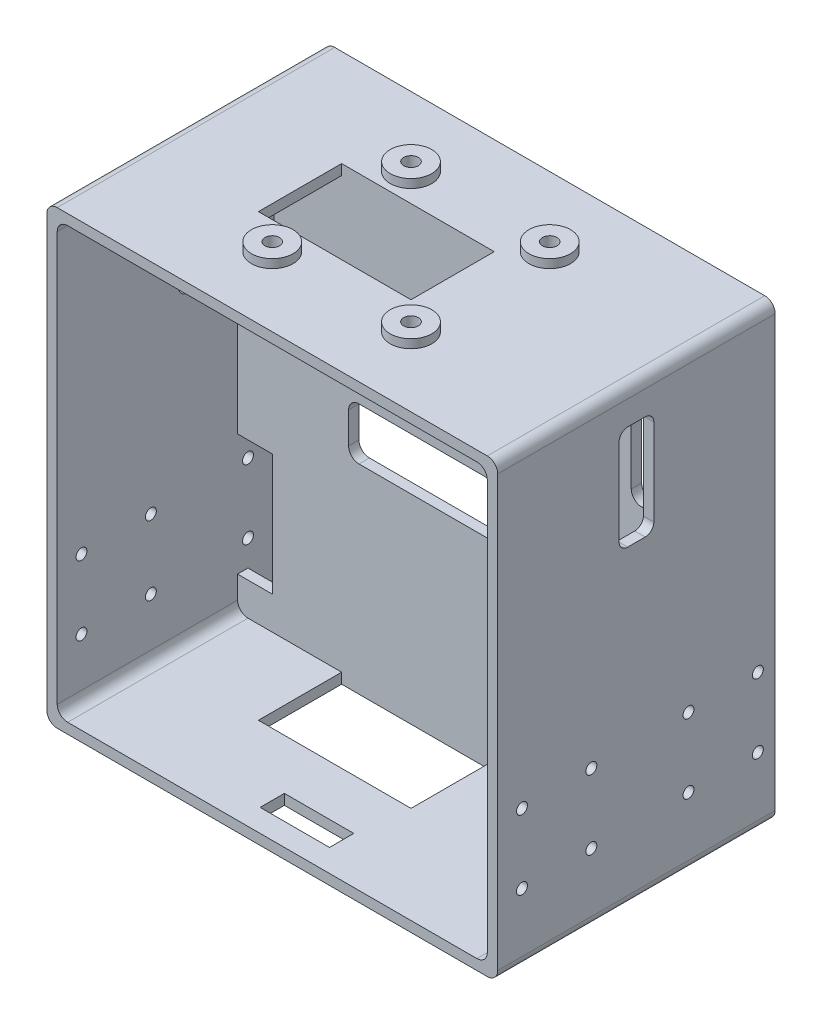
SolidWorks part; units mm, degrees
material "Du"
ref_plane "Front Plane" through (0, 0, 0) normal (0, 0, 1) x (1, 0, 0)
ref_plane "Top Plane" through (0, 0, 0) normal (0, 1, 0) x (1, 0, 0)
ref_plane "Right Plane" through (0, 0, 0) normal (1, 0, 0) x (0, 0, -1)
sketch "Sketch1" plane through (0, 0, 0) normal (0, 0, 1) x (1, 0, 0)
  line L1 (-65, 65) -> (65, 65)
  line L2 (-65, 65) -> (-65, -65)
  line L3 (-65, -65) -> (65, -65)
  line L4 (65, 65) -> (65, -65)
  line L5 (-65, 65) -> (65, -65) construction
  line L6 (-65, -65) -> (65, 65) construction
  line L7 (-62, 62) -> (62, 62)
  line L8 (-62, 62) -> (-62, -62)
  line L9 (-62, -62) -> (62, -62)
  line L10 (62, 62) -> (62, -62)
  line L11 (-62, 62) -> (62, -62) construction
  line L12 (-62, -62) -> (62, 62) construction
  point P0 (0, 0)
  point P6 (0, 0)
  dimension "D1" = 130
  dimension "D2" = 130
  dimension "D3" = 124
extrude "Boss-Extrude1" add sketch "Sketch1" along normal blind 80
fillet "Fillet1" radius 3 4 edges at (65, -65, 40) (-65, -65, 40) (-65, 65, 40) (65, 65, 40)
fillet "Fillet2" radius 3 4 edges at (62, -62, 40) (62, 62, 40) (-62, 62, 40) (-62, -62, 40)
sketch "Sketch2" plane through (0, -65, 0) normal (0, -1, 0) x (1, 0, 0)
  line L0 (-65, 0) -> (-65, 80) construction
  line L1 (-32, 52) -> (12, 52)
  line L2 (-32, 52) -> (-32, 28)
  line L3 (-32, 28) -> (12, 28)
  line L4 (12, 52) -> (12, 28)
  line L5 (-32, 52) -> (12, 28) construction
  line L6 (-32, 28) -> (12, 52) construction
  point P0 (-10, 40)
  dimension "D1" = 44
  dimension "D2" = 24
  dimension "D3" = 33
extrude "Cut-Extrude1" cut sketch "Sketch2" against normal through all
sketch "Sketch3" plane through (0, 0, 0) normal (0, 0, -1) x (-1, 0, 0)
  line L5 (-62, 62) -> (62, -62) construction
  line L6 (-62, -62) -> (62, 62) construction
  line L8 (-62, 62) -> (62, 62)
  line L9 (-62, 62) -> (-62, -62)
  line L10 (-62, -62) -> (62, -62)
  line L11 (62, 62) -> (62, -62)
  line L12 (-62, 62) -> (62, -62) construction
  line L13 (-62, -62) -> (62, 62) construction
  point P0 (0, 0)
  point P7 (0, 0)
sketch "Sketch4" plane through (0, 0, 0) normal (0, 0, -1) x (-1, 0, 0)
  line L1 (-62, 62) -> (62, 62)
  line L2 (-62, 62) -> (-62, -62)
  line L3 (-62, -62) -> (62, -62)
  line L4 (62, 62) -> (62, -62)
  line L5 (-62, 62) -> (62, -62) construction
  line L6 (-62, -62) -> (62, 62) construction
  point P0 (0, 0)
extrude "Boss-Extrude4" add sketch "Sketch4" against normal blind 28
extrude "Cut-Extrude2" cut sketch "Sketch3" against normal blind 25
fillet "Fillet3" radius 3 4 edges at (62, -62, 12.5) (-62, -62, 12.5) (-62, 62, 12.5) (62, 62, 12.5)
sketch "Sketch5" plane through (0, 0, 25) normal (0, 0, -1) x (-1, 0, 0)
  line L1 (-30, 7.5) -> (30, 7.5)
  line L2 (-30, 7.5) -> (-30, -7.5)
  line L3 (-30, -7.5) -> (30, -7.5)
  line L4 (30, 7.5) -> (30, -7.5)
  line L5 (-30, 7.5) -> (30, -7.5) construction
  line L6 (-30, -7.5) -> (30, 7.5) construction
  point P0 (0, 0)
  dimension "D1" = 60
  dimension "D2" = 15
extrude "Cut-Extrude3" cut sketch "Sketch5" against normal blind 25
ref_plane "Plane1" through (-30, -7.5, 25) normal (0, 0, -1) x (-1, 0, 0)
fillet "Fillet4" radius 3 4 edges at (30, 7.5, 26.5) (30, -7.5, 26.5) (-30, 7.5, 26.5) (-30, -7.5, 26.5)
sketch "Sketch7" plane through (0, 0, 25) normal (0, 0, -1) x (-1, 0, 0)
  line L0 (-62, -17.5) -> (-52, -17.5)
  line L1 (52, -17.5) -> (62, -17.5)
  line L2 (52, -17.5) -> (52, -52.5)
  line L3 (52, -52.5) -> (62, -52.5)
  line L4 (62, -17.5) -> (62, -52.5)
  line L5 (52, -17.5) -> (62, -52.5) construction
  line L6 (52, -52.5) -> (62, -17.5) construction
  line L7 (-62, -17.5) -> (-62, -52.5)
  line L8 (-62, -52.5) -> (-52, -52.5)
  line L9 (-52, -17.5) -> (-52, -52.5)
  line L10 (-62, -17.5) -> (-52, -52.5) construction
  line L11 (-62, -52.5) -> (-52, -17.5) construction
  line L12 (51.5, 47.5) -> (58.5, 47.5)
  line L13 (51.5, 47.5) -> (51.5, 22.5)
  line L14 (51.5, 22.5) -> (58.5, 22.5)
  line L15 (58.5, 47.5) -> (58.5, 22.5)
  line L16 (51.5, 47.5) -> (58.5, 22.5) construction
  line L17 (51.5, 22.5) -> (58.5, 47.5) construction
  line L18 (-58.5, 47.5) -> (-51.5, 47.5)
  line L19 (-58.5, 47.5) -> (-58.5, 22.5)
  line L20 (-58.5, 22.5) -> (-51.5, 22.5)
  line L21 (-51.5, 47.5) -> (-51.5, 22.5)
  line L22 (-58.5, 47.5) -> (-51.5, 22.5) construction
  line L23 (-58.5, 22.5) -> (-51.5, 47.5) construction
  point P0 (57, -35)
  point P6 (-57, -35)
  point P12 (55, 35)
  point P17 (-55, 35)
  dimension "D1" = 10
  dimension "D2" = 35
  dimension "D3" = 7
  dimension "D4" = 7
  dimension "D5" = 10
  dimension "D6" = 35
extrude "Cut-Extrude4" cut sketch "Sketch7" against normal through all
fillet "Fillet6" radius 3 8 edges at (51.5, 47.5, 26.5) (58.5, 47.5, 26.5) (51.5, 22.5, 26.5) (58.5, 22.5, 26.5) (-58.5, 47.5, 26.5) (-51.5, 47.5, 26.5) (-51.5, 22.5, 26.5) (-58.5, 22.5, 26.5)
sketch "Sketch8" plane through (65, 0, 0) normal (1, 0, 0) x (0, 0, -1)
  circle A0 centre (-5, -25) radius 1.575
  circle A1 centre (-5, -45) radius 1.575
  circle A2 centre (-25, -25) radius 1.575
  circle A3 centre (-25, -45) radius 1.575
  circle A4 centre (-53, -25) radius 1.575
  circle A5 centre (-53, -45) radius 1.575
  circle A6 centre (-73, -25) radius 1.575
  circle A7 centre (-73, -45) radius 1.575
  dimension "D1" = 3.15
sketch "Sketch10" plane through (-65, 0, 0) normal (-1, 0, 0) x (0, 0, 1)
  circle A0 centre (73, -25) radius 1.575
  circle A1 centre (73, -45) radius 1.575
  circle A2 centre (53, -25) radius 1.575
  circle A3 centre (53, -45) radius 1.575
  circle A4 centre (25, -25) radius 1.575
  circle A5 centre (25, -45) radius 1.575
  circle A6 centre (5, -25) radius 1.575
  circle A7 centre (5, -45) radius 1.575
  dimension "D1" = 3.15
extrude "Cut-Extrude8" cut sketch "Sketch8" against normal up to next
extrude "Cut-Extrude9" cut sketch "Sketch10" against normal up to next
sketch "Sketch11" plane through (0, 65, 0) normal (0, 1, 0) x (1, 0, 0)
  circle A0 centre (20, -20) radius 2.1
  circle A1 centre (-20, -20) radius 2.1
  circle A2 centre (-20, -60) radius 2.1
  circle A3 centre (20, -60) radius 2.1
  circle A4 centre (-20, -20) radius 6
  circle A5 centre (20, -20) radius 6
  circle A6 centre (20, -60) radius 6
  circle A7 centre (-20, -60) radius 6
  dimension "D1" = 4.2
  dimension "D9" = 12
  dimension "D10" = 12
  dimension "D11" = 12
  dimension "D12" = 12
  dimension "D2" = 40
  dimension "D3" = 40
  dimension "D4" = 40
  dimension "D5" = 40
  dimension "D6" = 20
  dimension "D7" = 20
  dimension "D8" = 20
  dimension "D13" = 20
extrude "Boss-Extrude5" add sketch "Sketch11" along normal blind 2.5
sketch "Sketch13" plane through (0, 65, 0) normal (0, 1, 0) x (1, 0, 0)
  circle A0 centre (-20, -20) radius 2.1
  circle A1 centre (20, -20) radius 2.1
  circle A2 centre (20, -60) radius 2.1
  circle A3 centre (-20, -60) radius 2.1
extrude "Cut-Extrude11" cut sketch "Sketch13" against normal up to next
sketch "Sketch14" plane through (65, 0, 0) normal (1, 0, 0) x (0, 0, -1)
  line L1 (-45, 55) -> (-35, 55)
  line L2 (-45, 55) -> (-45, 25)
  line L3 (-45, 25) -> (-35, 25)
  line L4 (-35, 55) -> (-35, 25)
  line L5 (-45, 55) -> (-35, 25) construction
  line L6 (-45, 25) -> (-35, 55) construction
  point P0 (-40, 40)
  dimension "D1" = 30
  dimension "D2" = 10
extrude "Cut-Extrude12" cut sketch "Sketch14" against normal through all
fillet "Fillet7" radius 2.5 4 edges at (63.5, 55, 45) (63.5, 55, 35) (63.5, 25, 35) (63.5, 25, 45)
fillet "Fillet8" radius 2.5 4 edges at (-63.5, 55, 35) (-63.5, 55, 45) (-63.5, 25, 45) (-63.5, 25, 35)
sketch "Sketch15" plane through (0, -65, 0) normal (0, -1, 0) x (-1, 0, 0)
  line L1 (10, -73.5) -> (-10, -73.5)
  line L2 (10, -73.5) -> (10, -66.5)
  line L3 (10, -66.5) -> (-10, -66.5)
  line L4 (-10, -73.5) -> (-10, -66.5)
  line L5 (10, -73.5) -> (-10, -66.5) construction
  line L6 (10, -66.5) -> (-10, -73.5) construction
  point P0 (0, -70)
  dimension "D1" = 20
  dimension "D2" = 7
extrude "Cut-Extrude13" cut sketch "Sketch15" against normal up to next
